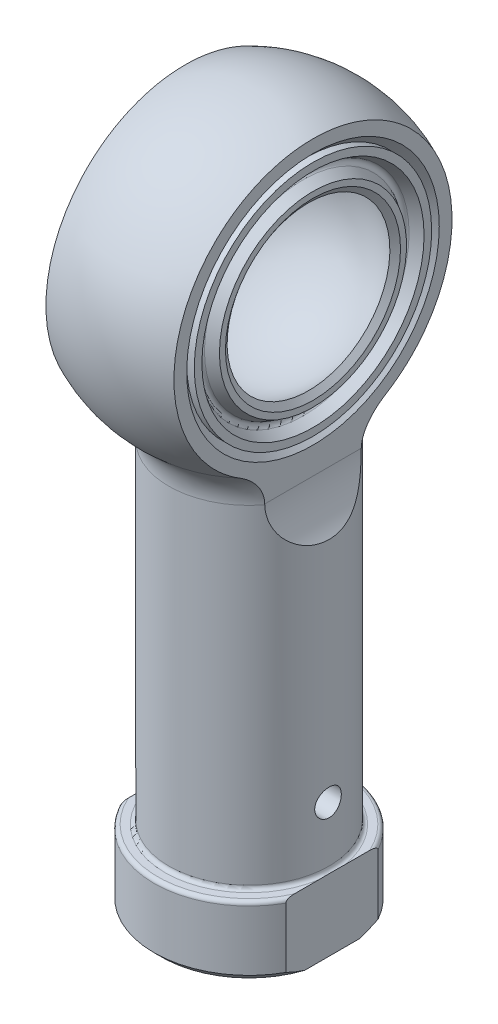
SolidWorks part; units mm, degrees
material "AISI 316 Annealed Stainless Steel Bar (SS)"
ref_plane "Front Plane" through (0, 0, 0) normal (0, 0, 1) x (1, 0, 0)
ref_plane "Top Plane" through (0, 0, 0) normal (0, 1, 0) x (1, 0, 0)
ref_plane "Right Plane" through (0, 0, 0) normal (1, 0, 0) x (0, 0, -1)
sketch "Sketch1" plane through (0, 0, 0) normal (0, 0, 1) x (1, 0, 0)
  line L0 (0, -1004.5939) -> (0, 0) construction
  line L1 (3.5719, 0) -> (6.35, 0)
  line L2 (6.35, 0) -> (6.35, 4.7752)
  line L3 (6.35, 4.7752) -> (5.3594, 4.7752)
  line L4 (5.3594, 4.7752) -> (5.3594, 28.5916)
  line L5 (0, 37.3126) -> (0, 47.5488)
  line L6 (3.5719, 0) -> (3.5719, 19.05)
  line L7 (3.5719, 19.05) -> (3.3179, 19.05)
  line L8 (3.3179, 19.05) -> (3.3179, 22.225)
  line L9 (3.3179, 22.225) -> (0.889, 23.6844)
  line L10 (0.889, 23.6844) -> (0.889, 36.4236)
  line L11 (0.889, 36.4236) -> (0, 37.3126)
  arc A0 (0, 47.5488) -> (5.3594, 28.5916) centre (0, 37.3126) cw
  dimension "D" = 20.4724
  dimension "A" = 37.3126
  dimension "E" = 10.7188
  dimension "K" = 12.7
  dimension "F" = 4.7752
  dimension "Thread" = 7.1437
  dimension "C" = 19.05
  dimension "D1" = 59
  dimension "D2" = 1.778
  dimension "P" = 22.225
  dimension "D3" = 0.254
  dimension "D4" = 45
revolve "Revolve1" add sketch "Sketch1" angle 360 about L0
chamfer "Chamfer1" distance 0.508 angle 45 1 edges at (0, 0, -6.35)
fillet "Fillet1" radius 3.048 1 edges at (0, 28.5916, -5.3594)
fillet "Fillet2" radius 0.254 2 edges at (0, 4.7752, -6.35) (0, 4.7752, -5.3594)
sketch "Sketch2" plane through (0, 0, 0) normal (0, 0, 1) x (1, 0, 0)
  line L0 (-5.5499, 0) -> (5.5499, 0)
  line L1 (5.5499, 0) -> (5.5499, 23.7163)
  line L2 (-5.5499, 0) -> (-5.5499, 23.7163)
  line L3 (-4.2799, 47.5488) -> (4.2799, 47.5488)
  line L4 (4.2799, 47.5488) -> (4.2799, 27.0764)
  line L5 (-4.2799, 47.5488) -> (-4.2799, 27.0764)
  line L6 (-4.2799, 27.0764) -> (4.2799, 27.0764) construction
  arc A0 (-4.2799, 27.0764) -> (-5.5499, 23.7163) centre (-9.3599, 27.0764) cw
  arc A1 (4.2799, 27.0764) -> (5.5499, 23.7163) centre (9.3599, 27.0764) ccw
  arc A2 (6.4784, 29.3873) -> (-6.4784, 29.3873) centre (0, 37.3126) ccw construction
  arc A3 (5.3594, 28.5916) -> (0, 47.5488) centre (0, 37.3126) ccw construction
  dimension "D1" = 5.08
  dimension "J" = 11.0998
  dimension "H" = 8.5598
extrude "Cut-Extrude1" cut sketch "Sketch2" against normal through all both and the other way through all flip side to cut
sketch "Sketch3" plane through (0, 0, 0) normal (1, 0, 0) x (0, 0, -1)
  circle A0 centre (0, 37.3126) radius 7.9375
  arc A1 (0, 47.5488) -> (-6.4784, 29.3873) centre (0, 37.3126) ccw construction
  circle A2 centre (0, 8.7186) radius 0.889
  dimension "D1" = 1.778
  dimension "S" = 15.875
  dimension "D2" = 8.7186
extrude "Cut-Extrude2" cut sketch "Sketch3" against normal through all both and the other way through all
sketch "Sketch4" plane through (0, 0, 0) normal (0, 0, 1) x (1, 0, 0)
  line L0 (-14.4492, 37.3126) -> (16.2709, 37.3126) construction
  line L1 (-4.2799, 37.3126) -> (4.2799, 37.3126) construction
  line L2 (3.9801, 42.7565) -> (4.2799, 43.1666)
  line L3 (4.2799, 43.1666) -> (4.2799, 43.5689)
  line L4 (4.2799, 45.2501) -> (-4.2799, 45.2501)
  line L5 (-4.2799, 45.2501) -> (-4.2799, 44.7421)
  line L6 (-4.2799, 43.1666) -> (-3.9801, 42.7565)
  line L7 (4.2799, 45.2501) -> (-4.2799, 45.2501) construction
  line L8 (4.2799, 29.3873) -> (4.2799, 46.6111) construction
  line L9 (-4.2799, 46.6111) -> (-4.2799, 29.3873) construction
  line L10 (4.2799, 44.7421) -> (3.6449, 44.3755)
  line L11 (3.6449, 43.9355) -> (4.2799, 43.5689)
  line L12 (4.2799, 44.7421) -> (4.2799, 45.2501)
  line L13 (-4.2799, 44.7421) -> (-3.6449, 44.3755)
  line L14 (-3.6449, 43.9355) -> (-4.2799, 43.5689)
  line L15 (-4.2799, 43.5689) -> (-4.2799, 43.1666)
  arc A0 (-3.9801, 42.7565) -> (3.9801, 42.7565) centre (0, 37.3126) cw
  arc A1 (0, 47.5488) -> (-4.2799, 46.6111) centre (0, 37.3126) ccw construction
  arc A2 (3.6449, 44.3755) -> (3.6449, 43.9355) centre (3.7719, 44.1555) ccw
  arc A3 (-3.6449, 44.3755) -> (-3.6449, 43.9355) centre (-3.7719, 44.1555) cw
  dimension "D1" = 0.508
  dimension "Ball_Dia" = 13.4874
  dimension "D2" = 0.254
  dimension "D3" = 0.508
  dimension "D4" = 0.762
  dimension "D5" = 60
revolve "Revolve2" add sketch "Sketch4" angle 360 about L0
chamfer "Chamfer2" distance 0.508 angle 45 2 edges at (-4.2799, 29.3751, 0) (4.2799, 45.2501, 0)
equation "\"D2@Sketch3\"=\"Thread@Sketch1\"+.062"
